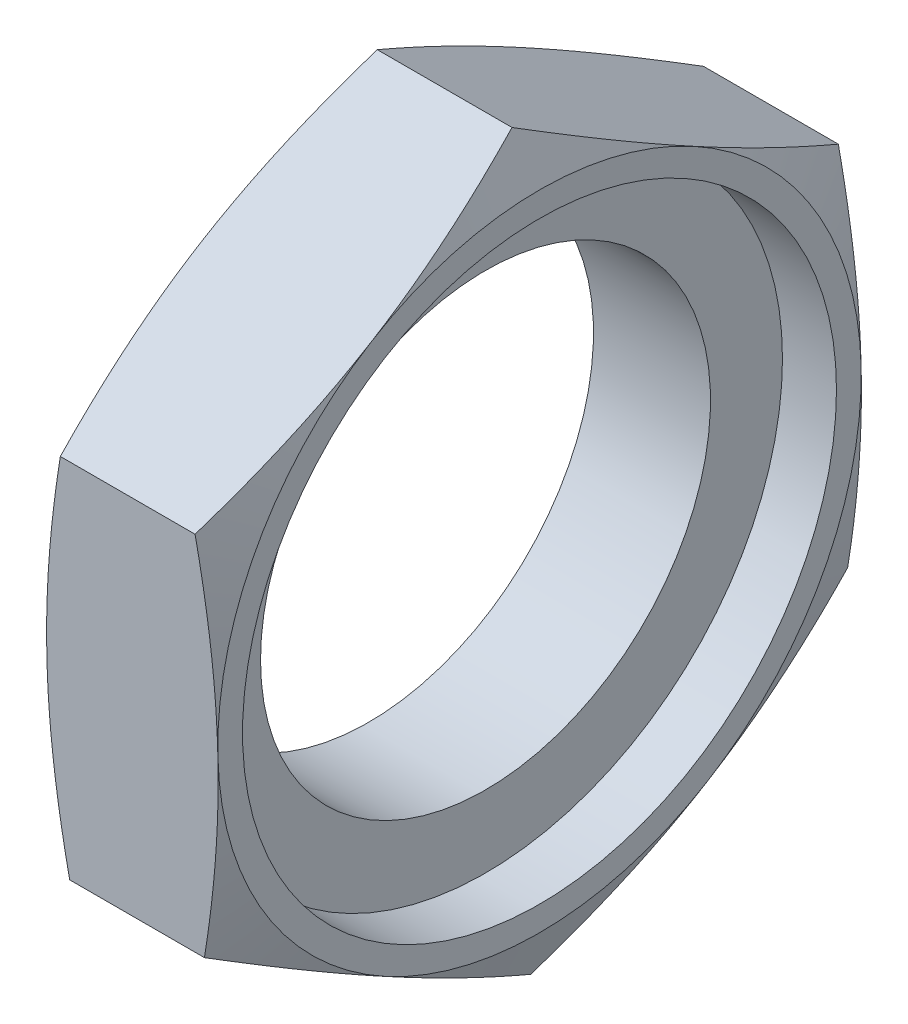
SolidWorks part; units mm, degrees
material "AISI 1020"
ref_plane "Plano superior" through (0, 0, 0) normal (0, 0, 1) x (1, 0, 0)
ref_plane "Plano frontal" through (0, 0, 0) normal (0, 1, 0) x (1, 0, 0)
ref_plane "Plano direito" through (0, 0, 0) normal (1, 0, 0) x (0, 0, -1)
sketch "Esboço1" plane through (0, 0, 0) normal (1, 0, 0) x (0, 0, -1)
  line L1 (14.0875, 8.6137) -> (-0.416, 16.507)
  line L2 (-0.416, 16.507) -> (-14.5034, 7.8932)
  line L3 (-14.5034, 7.8932) -> (-14.0875, -8.6137)
  line L4 (-14.0875, -8.6137) -> (0.416, -16.507)
  line L5 (0.416, -16.507) -> (14.5034, -7.8932)
  line L6 (14.5034, -7.8932) -> (14.0875, 8.6137)
  circle A0 centre (0, 0) radius 14.3 construction
  circle A1 centre (0, 0) radius 10
  dimension "D1" = 28.6
  dimension "D2" = 20
extrude "Ressalto-extrusão1" add sketch "Esboço1" along normal blind 7.6
cosmetic thread "Representação de rosca2" parameters "D2"=22
sketch "Esboço3" plane through (0, 0, 0) normal (-1, 0, 0) x (0, 0, 1)
  circle A0 centre (0, 0) radius 14.3
sketch "Esboço4" plane through (7.6, 0, 0) normal (1, 0, 0) x (0, 0, -1)
  circle A0 centre (0, 0) radius 14.3
hole_wizard "Furo1" positions "Esboço5" profile "Esboço6" legacy
sketch "Esboço5" plane through (7.6, 0, 0) normal (1, 0, 0) x (0, 0, -1)
  point P0 (0, 0)
  point P3 (0, 0)
sketch "Esboço6" plane through (7.6, 0, 0) normal (0, 1, 0) x (0, 0, -1)
  line L0 (0, 0) -> (0, 2.4)
  line L1 (0, 2.4) -> (13.2, 2.4)
  line L2 (13.2, 2.4) -> (13.2, 0)
  line L3 (13.2, 0) -> (0, 0)
  line L4 (0, 110) -> (0, -10) construction
  dimension "Diameter" = 26.4
  dimension "Depth" = 2.4
sketch "Esboço7" plane through (7.6, 0, 0) normal (1, 0, 0) x (0, 0, -1)
  circle A0 centre (0, 0) radius 14.3
extrude "Corte-extrusão1" cut sketch "Esboço7" against normal blind 13 draft 70 flip side to cut
sketch "Esboço8" plane through (0, 0, 0) normal (-1, 0, 0) x (0, 0, 1)
  circle A0 centre (0, 0) radius 14.3
extrude "Corte-extrusão2" cut sketch "Esboço8" against normal blind 13 draft 70 flip side to cut
